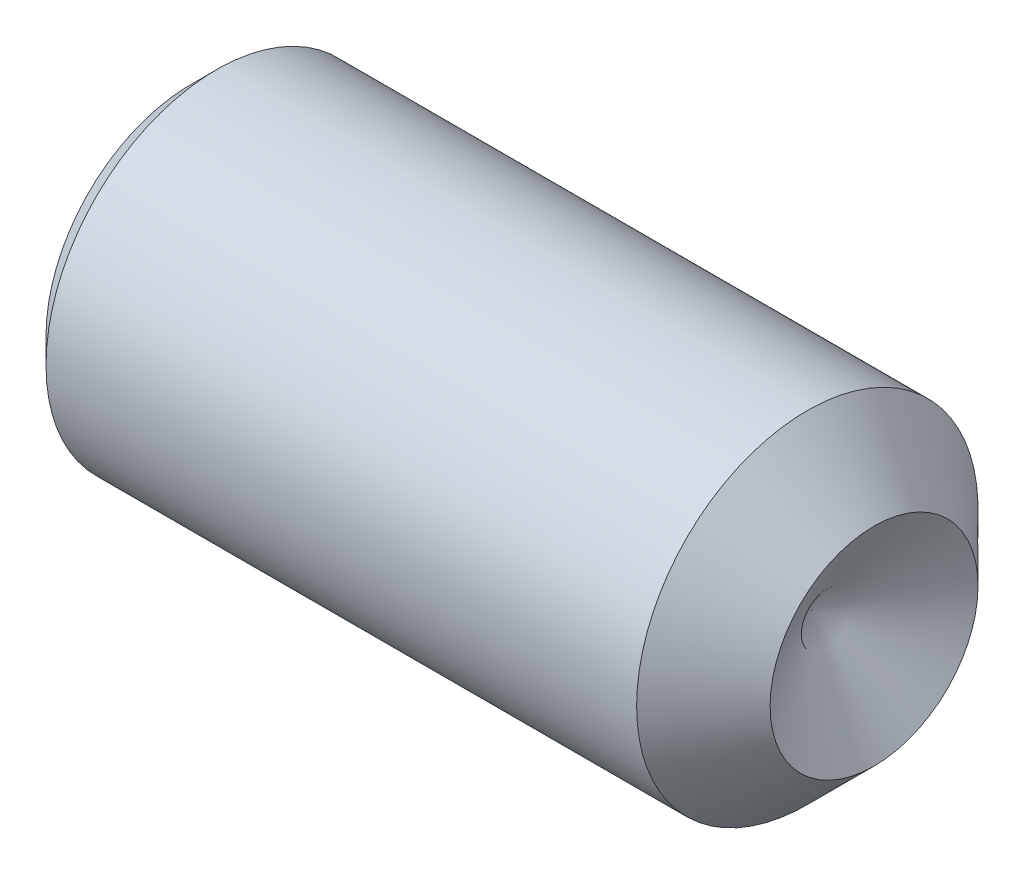
SolidWorks part; units mm, degrees
revolve "BaseBody" add sketch "BodySke" angle 360 about L5
sketch "BodySke" plane through (0, 0, 0) normal (0, 0, 1) x (1, 0, 0)
  line L0 (0, 0) -> (0, 10.8102)
  line L1 (0, 10.8102) -> (1.8898, 12.7)
  line L2 (1.8898, 12.7) -> (45.8343, 12.7)
  line L3 (45.8343, 12.7) -> (50.8, 7.7343)
  line L4 (46.1528, 0) -> (0, 0)
  line L5 (-12.7, 0) -> (88.9, 0) construction
  line L6 (46.1528, 0) -> (50.8, 7.7343)
  line L7 (50.8, 7.7343) -> (50.8, 17.2593) construction
  line L8 (0, -10.8102) -> (1.8898, -12.7) construction
  line L9 (46.1528, 0) -> (50.8, -7.7343) construction
  line L10 (45.8343, -12.7) -> (50.8, -7.7343) construction
  line L11 (2.1082, 15.875) -> (2.1082, -3.175) construction
  dimension "Diameter" = 25.4
  dimension "Drive_ch_ang" = 45
  dimension "Minor_dia" = 21.6205
  dimension "Cup_nose_ang" = 45
  dimension "Cup_ang" = 118
  dimension "Cup_dia" = 15.4686
  dimension "Length" = 50.8
  dimension "Advance" = 2.1082
cosmetic thread "ThreadCosmetic" [suppressed] parameters "Thread_minor"=21.6205
ref_plane "Plane1" through (0, 0, 0) normal (0, 0, 1) x (1, 0, 0)
ref_plane "Plane2" through (0, 0, 0) normal (0, 1, 0) x (1, 0, 0)
ref_plane "Plane3" through (0, 0, 0) normal (1, 0, 0) x (0, 0, -1)
sketch "Sketch2" plane through (0, 0, 0) normal (-1, 0, 0) x (0, 0, 1)
  line L0 (4.1208, 7.1374) -> (-4.1208, 7.1374)
  line L1 (-4.1208, 7.1374) -> (-8.2416, 0)
  line L2 (4.1208, 7.1374) -> (8.2416, 0)
  line L3 (4.1208, -7.1374) -> (8.2416, 0)
  line L4 (4.1208, -7.1374) -> (-4.1208, -7.1374)
  line L5 (-4.1208, -7.1374) -> (-8.2416, 0)
  dimension "Hex_size" = 14.2748
  dimension "D2" = 7.1374
  dimension "D3" = 7.1374
extrude "Hex" cut sketch "Sketch2" against normal blind 14.2748
sketch "Sketch4" plane through (0, 4.7709, -0.5249) normal (-1, 0, 0) x (0, 0, 1)
  line L0 (0.5249, -4.7709) -> (10.6976, -4.7709)
  line L1 (0.5249, -4.7709) -> (6.6732, -1.2211) construction
  line L2 (0.5249, -4.7709) -> (5.6112, 4.0389)
  line L3 (8.9666, -2.6687) -> (10.2861, -1.9069)
  line L4 (6.5663, 1.4888) -> (7.8858, 2.2506)
  arc A0 (8.9666, -2.6687) -> (6.5663, 1.4888) centre (0.5249, -4.7709) ccw
  arc A1 (10.6976, -4.7709) -> (10.2861, -1.9069) centre (0.5249, -4.7709) ccw
  arc A2 (5.6112, 4.0389) -> (7.8858, 2.2506) centre (0.5249, -4.7709) cw
  circle A3 centre (0.5249, -4.7709) radius 8.6995 construction
  circle A4 centre (0.5249, -4.7709) radius 10.1727 construction
  dimension "Spline_n_dim" = 17.399
  dimension "Spline_m_dim" = 20.3454
  dimension "D1" = 30
  dimension "Spline_a_dim" = 60
  dimension "Spline_p_dim" = 4.8006
  dimension "D3" = 2.4003
extrude "Spline" [suppressed] cut sketch "Sketch4" against normal blind 12.7
pattern_circular "CirPattern1" [suppressed] count 6 every 60 about axis through (-12.7, 0, 0) along (1, 0, 0)
sketch "ThdSchSke" plane through (0, 0, 0) normal (0, 0, 1) x (1, 0, 0)
  line L0 (1.8898, -10.8102) -> (0.5665, -12.7)
  line L1 (1.8898, -10.8102) -> (3.213, -12.7)
  line L2 (3.213, -12.7) -> (3.213, -15.875)
  line L3 (-3.175, 0) -> (5.1513, 0) construction
  line L4 (1.8898, 12.7) -> (1.8898, -12.7) construction
  line L5 (3.213, -15.875) -> (0.5665, -15.875)
  line L6 (0.5665, -15.875) -> (0.5665, -12.7)
  dimension "Thread_minor" = 21.6205
  dimension "Diameter" = 25.4
revolve "ThreadSchematic" [suppressed] cut sketch "ThdSchSke" angle 360 about L3
pattern_linear "ThdSchPat" [suppressed]
equation "\"D2@Sketch2\" = \"Hex_size@Sketch2\" / 2"
equation "\"D3@Sketch2\" = \"Hex_size@Sketch2\" / 2"
equation "\"Thread_minor@ThreadCosmetic\" = \"Minor_dia@BodySke\""
equation "\"D1@Sketch4\" = \"Spline_a_dim@Sketch4\" / 2"
equation "\"D3@Sketch4\" = \"Spline_p_dim@Sketch4\" / 2"
equation "\"D2@CirPattern1\" = \"Spline_a_dim@Sketch4\""
equation "\"Num_teeth@CirPattern1\" = 360 / \"D2@CirPattern1\""
equation "\"Thread_minor@ThdSchSke\" = \"Thread_minor@ThreadCosmetic\""
equation "\"Diameter@ThdSchSke\" = \"Diameter@BodySke\""
equation "\"Overcut@ThdSchSke\" = \"Diameter@BodySke\" * 1.25"
equation "\"Num_threads@ThdSchPat\" = int( (\"Length@BodySke\" - ( ( ( \"Diameter@BodySke\" - \"Minor_dia@BodySke\" ) * 0.5 ) / tan( \"Drive_ch_ang@BodySke\" * 0.017453292 ) ) - ( ( ( \"Diameter@BodySke\" - \"Cup_dia@BodySke\" ) * 0.5 ) * tan( \"Cup_nose_ang@BodySke\" * 0.017453292 ) ) ) / \"Advance@BodySke\" + 0.999 )  + 1"
equation "\"Advance@ThdSchPat\" = (\"Length@BodySke\" - ( ( ( \"Diameter@BodySke\" - \"Minor_dia@BodySke\" ) * 0.5 ) / tan( \"Drive_ch_ang@BodySke\" * 0.017453292 ) ) - ( ( ( \"Diameter@BodySke\" - \"Cup_dia@BodySke\" ) * 0.5 ) * tan( \"Cup_nose_ang@BodySke\" * 0.017453292 ) ) ) /  (\"Num_threads@ThdSchPat\" - 1) 'relax it"
equation "' \"Num_threads@ThdSchPat\" = \"Num_threads@ThdSchPat\" - sgn( \"Num_threads@ThdSchPat\" - 1) '---chamfered tips only---"
